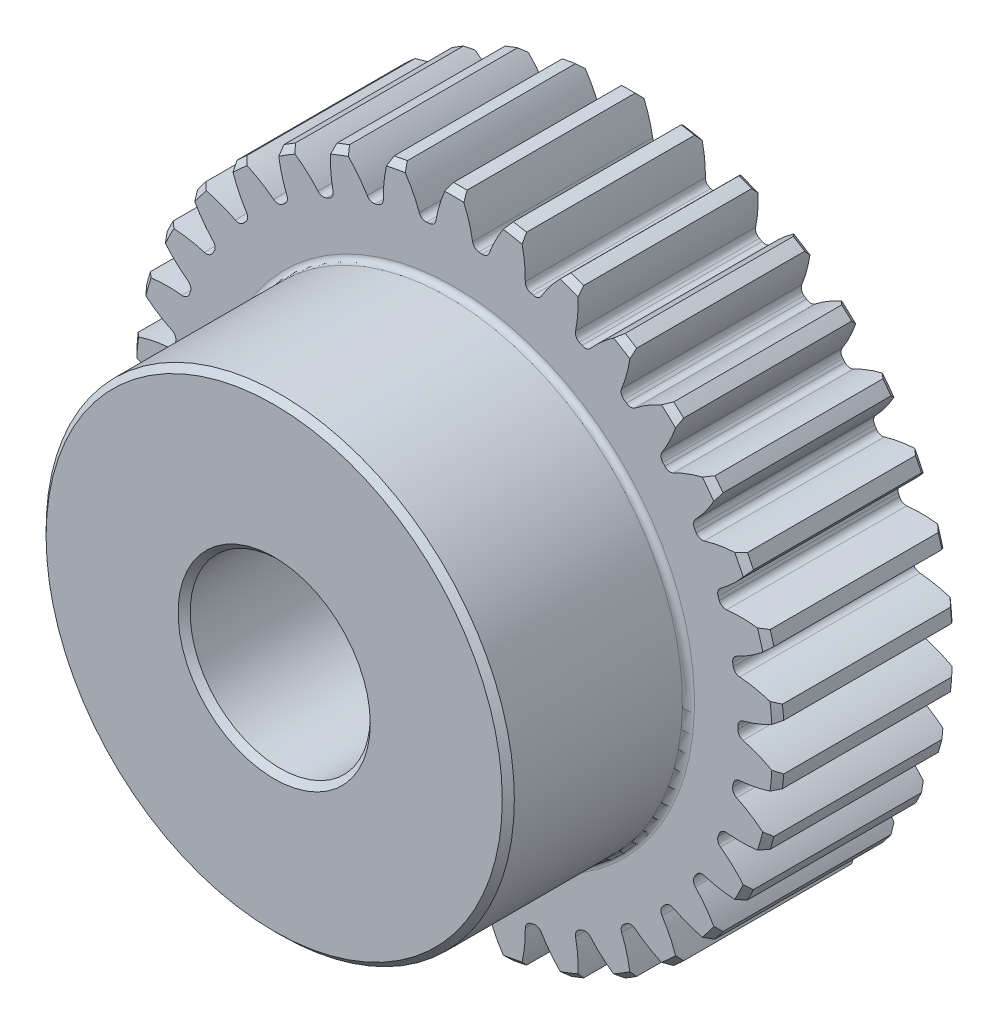
SolidWorks part; units mm, degrees
ref_plane "Front Plane" through (0, 0, 0) normal (0, 0, 1) x (1, 0, 0)
ref_plane "Top Plane" through (0, 0, 0) normal (0, 1, 0) x (1, 0, 0)
ref_plane "Right Plane" through (0, 0, 0) normal (1, 0, 0) x (0, 0, -1)
sketch "Sketch1" plane through (0, 0, 0) normal (0, 0, 1) x (1, 0, 0)
  line L0 (0, 0) -> (0, 17) construction
  line L1 (-5.4637, 18.9886) -> (5.4637, 15.0114) construction
  circle A0 centre (0, 0) radius 15.75 construction
  circle A1 centre (0, 0) radius 18 construction
  circle A2 centre (0, 0) radius 17 construction
  circle A3 centre (0, 0) radius 15.9748 construction
  circle A4 centre (0, 0) radius 13 construction
  circle A5 centre (0, 0) radius 5 construction
  point P8 (0.5, 0)
  point P13 (17, 0)
  dimension "OD" = 36
  dimension "Root Diameter" = 31.5
  dimension "Gear Pitch Diameter" = 34
  dimension "Base Diameter" = 31.9495
  dimension "Hub Diameter" = 26
  dimension "For Shaft Diameter" = 10
  dimension "Pressure Angle" = 20
  dimension "Number of Teeth" = 34
  dimension "Module" = 1
sketch "Sketch2" plane through (0, 0, 0) normal (1, 0, 0) x (0, 0, -1)
  line L0 (-10, 0) -> (10, 0) construction
  line L1 (10, 18) -> (10, -18) construction
  line L2 (0, -13) -> (-10, -13) construction
  line L3 (-10, 18) -> (10, 18) construction
  line L8 (-10, -13) -> (-10, 13) construction
  point P4 (0, 18)
  point P5 (-5, 0)
  dimension "Overall Width" = 20
  dimension "Hub Width" = 10
  dimension "Approx Set Screw Positon" = 5
  dimension "Face Width" = 10
sketch "Sketch3" plane through (0, 0, 0) normal (0, 0, 1) x (1, 0, 0)
  circle A0 centre (0, 0) radius 18
  circle A1 centre (0, 0) radius 18 construction
extrude "Boss-Extrude1" add sketch "Sketch3" against normal up to vertex (10 mm away) and the other way up to vertex (10 mm away) up to point (0, 0, -10) other way up to point (0, 0, 10)
sketch "Sketch5" plane through (0, 0, 0) normal (1, 0, 0) x (0, 0, -1)
  line L1 (0, 13) -> (-10, 13)
  line L2 (0, 13) -> (0, 18)
  line L3 (0, 18) -> (-10, 18)
  line L4 (-10, 13) -> (-10, 18)
  line L5 (-10, 0) -> (10, 0)
  line L6 (-10, 0) -> (-10, 5)
  line L7 (-10, 5) -> (10, 5)
  line L8 (10, 0) -> (10, 5)
  point P5 (0, 13)
  point P12 (0, 5)
revolve "Cut-Revolve1" cut sketch "Sketch5" angle 360 about L0
fillet "Fillet2" radius 0.3355 1 edges at (0, -13, 0)
chamfer "Chamfer1" distance 0.3355 angle 45 5 edges at (0, -5, -10) (0, -18, 0) (18, 0, -10) (0, -5, 10) (0, -13, 10)
sketch "Sketch4" plane through (0, 0, 0) normal (0, 0, 1) x (1, 0, 0)
  line L0 (15.7451, 0.3927) -> (15.7451, -0.3927)
  arc A3 (17.9539, 1.288) -> (17.9539, -1.288) centre (0, 0) cw
  circle A4 centre (0, 0) radius 18 construction
  arc A5 (15.7451, 0.3927) -> (17.9539, 1.288) centre (14.1683, 7.4547) ccw
  circle A8 centre (0, 0) radius 15.75 construction
  arc A9 (15.7451, -0.3927) -> (17.9539, -1.288) centre (14.1683, -7.4547) cw
  spline S0 degree 4 poles (15.967, 0.4999) (15.9701, 0.5) (15.9791, 0.5005) (15.9959, 0.5018) (16.0234, 0.5046) (16.0583, 0.5091) (16.1034, 0.5159) (16.1565, 0.5252) (16.2147, 0.5368) (16.2779, 0.551) (16.3409, 0.5664) (16.4036, 0.583) (16.4659, 0.6006) (16.5413, 0.6233) (16.6315, 0.6523) (16.7366, 0.6889) (16.8555, 0.7334) (16.9763, 0.7822) (17.0947, 0.8329) (17.2139, 0.8872) (17.329, 0.942) (17.448, 1.0022) (17.5576, 1.0593) (17.6798, 1.1269) (17.7783, 1.1824) (17.9076, 1.2595) (17.9837, 1.3061) (18.0726, 1.362) (18.112, 1.3875) (18.1362, 1.4032) knots 0 0 0 0 0 0.005377 0.015084 0.028532 0.04661 0.064855 0.092111 0.119476 0.146842 0.174209 0.201575 0.228941 0.256307 0.307035 0.361767 0.4165 0.471232 0.525964 0.580697 0.635429 0.690161 0.744894 0.799626 0.854358 0.909091 0.954545 1 1 1 1 1 construction
  spline S1 degree 4 poles (15.967, 0.4999) (15.9701, 0.5) (15.9791, 0.5005) (15.9959, 0.5018) (16.0234, 0.5046) (16.0583, 0.5091) (16.1034, 0.5159) (16.1565, 0.5252) (16.2147, 0.5368) (16.2779, 0.551) (16.3409, 0.5664) (16.4036, 0.583) (16.4659, 0.6006) (16.5413, 0.6233) (16.6315, 0.6523) (16.7366, 0.6889) (16.8555, 0.7334) (16.9763, 0.7822) (17.0947, 0.8329) (17.2139, 0.8872) (17.329, 0.942) (17.448, 1.0022) (17.5576, 1.0593) (17.6798, 1.1269) (17.7783, 1.1824) (17.8795, 1.2428) (17.9287, 1.2726) (17.9539, 1.288) knots 0 0 0 0 0 0.005377 0.015084 0.028532 0.04661 0.064855 0.092111 0.119476 0.146842 0.174209 0.201575 0.228941 0.256307 0.307035 0.361767 0.4165 0.471232 0.525964 0.580697 0.635429 0.690161 0.744894 0.799626 0.854358 0.909091 0.909091 0.909091 0.909091 0.909091 construction
  spline S2 degree 4 poles (15.967, -0.4999) (15.9701, -0.5) (15.9791, -0.5005) (15.9959, -0.5018) (16.0234, -0.5046) (16.0583, -0.5091) (16.1034, -0.5159) (16.1565, -0.5252) (16.2147, -0.5368) (16.2779, -0.551) (16.3409, -0.5664) (16.4036, -0.583) (16.4659, -0.6006) (16.5413, -0.6233) (16.6315, -0.6523) (16.7366, -0.6889) (16.8555, -0.7334) (16.9763, -0.7822) (17.0947, -0.8329) (17.2139, -0.8872) (17.329, -0.942) (17.448, -1.0022) (17.5576, -1.0593) (17.6798, -1.1269) (17.7783, -1.1824) (17.9076, -1.2595) (17.9837, -1.3061) (18.0726, -1.362) (18.112, -1.3875) (18.1362, -1.4032) knots 0 0 0 0 0 0.005377 0.015084 0.028532 0.04661 0.064855 0.092111 0.119476 0.146842 0.174209 0.201575 0.228941 0.256307 0.307035 0.361767 0.4165 0.471232 0.525964 0.580697 0.635429 0.690161 0.744894 0.799626 0.854358 0.909091 0.954545 1 1 1 1 1 construction
  spline S3 degree 4 poles (15.967, -0.4999) (15.9701, -0.5) (15.9791, -0.5005) (15.9959, -0.5018) (16.0234, -0.5046) (16.0583, -0.5091) (16.1034, -0.5159) (16.1565, -0.5252) (16.2147, -0.5368) (16.2779, -0.551) (16.3409, -0.5664) (16.4036, -0.583) (16.4659, -0.6006) (16.5413, -0.6233) (16.6315, -0.6523) (16.7366, -0.6889) (16.8555, -0.7334) (16.9763, -0.7822) (17.0947, -0.8329) (17.2139, -0.8872) (17.329, -0.942) (17.448, -1.0022) (17.5576, -1.0593) (17.6798, -1.1269) (17.7783, -1.1824) (17.8795, -1.2428) (17.9287, -1.2726) (17.9539, -1.288) knots 0 0 0 0 0 0.005377 0.015084 0.028532 0.04661 0.064855 0.092111 0.119476 0.146842 0.174209 0.201575 0.228941 0.256307 0.307035 0.361767 0.4165 0.471232 0.525964 0.580697 0.635429 0.690161 0.744894 0.799626 0.854358 0.909091 0.909091 0.909091 0.909091 0.909091 construction
  dimension "D1" = 0.7854
extrude "Cut-Extrude1" cut sketch "Sketch4" against normal through all both and the other way through all
fillet "Fillet1" radius 0.3927 2 edges at (15.7451, 0.3927, -5) (15.7451, -0.3927, -5)
pattern_circular "CirPattern1" count 34 over 360 about axis through (0, 0, 0) along (0, 0, 1) of "Cut-Extrude1", "Fillet1"
equation "\"Number of Teeth\"= 34"
equation "\"Module\"= 1"
equation "\"Diametral Pitch\"= 1 / \"Module\""
equation "\"Dedendum\"= 1.25 / \"Diametral Pitch\""
equation "\"Pitch Diameter\"= \"Module\" * \"Number of Teeth\""
equation "\"Root Diameter\"= \"Pitch Diameter\" - ( 2 * \"Dedendum\" )"
equation "\"Root Diameter@Sketch1\"=\"Root Diameter\""
equation "\"OD@Sketch1\" = \"Outside Diameter\""
equation "\"D1@CirPattern1\"=\"Number of Teeth\""
equation "\"Pressure Angle\"=20"
equation "\"Base Diameter\"= \"Pitch Diameter\" * cos ( \"Pressure Angle\" )"
equation "\"Outside Diameter\"= ( \"Number of Teeth\" + 2 ) / \"Diametral Pitch\""
equation "\"Pitch Angle\"= 360deg / \"Number of Teeth\""
equation "\"Alpha\"= sqr ( \"Pitch Diameter\" ^ 2 - \"Base Diameter\" ^ 2 ) / \"Base Diameter\" * 180 / PI - \"Pressure Angle\""
equation "\"Beta\"= ( \"Pitch Angle\" / 4 - \"Alpha\" )"
equation "\"Phi\"= sqr ( ( \"Outside Diameter\" / 2 ) ^ 2 - ( \"Base Diameter\" / 2 ) ^ 2 ) / ( \"Base Diameter\" / 2 )"
equation "\"Addendum\"= 1 / \"Diametral Pitch\""
equation "\"WorkingDepth\"= 2 / \"Diametral Pitch\""
equation "\"WholeDepth\"= 2.25 / \"Diametral Pitch\""
equation "\"Clearance\"= 0.25 / \"Diametral Pitch\""
equation "\"ToothThickness\"= ( pi * 2 ) / \"Diametral Pitch\""
equation "\"CircularPitch\"= pi / \"Diametral Pitch\""
equation "\"Number of Teeth@Sketch1\"=\"Number of Teeth\""
equation "\"Module@Sketch1\"=\"Module\""
equation "\"Pressure Angle@Sketch1\"=\"Pressure Angle\""
equation "\"Gear Pitch Diameter@Sketch1\"=\"Pitch Diameter\""
equation "\"Base Diameter@Sketch1\"=\"Base Diameter\""
equation "\"Fillet\"= \"Clearance\" * cos ( \"Pressure Angle\" ) * tan ( ( 90 + \"Pressure Angle\" ) / 2 )"
equation "\"D1@Fillet2\"=\"Fillet\""
equation "\"Approx Set Screw Positon@Sketch2\" = \"Hub Width@Sketch2\" / 2"
equation "\"D2\"= \"Fillet\" * 2"
equation "\"D1@Chamfer1\"=\"Fillet\""
equation "\"D1@Sketch4\"=\"CircularPitch\"*0.25"
equation "\"D1@Fillet1\"=\"CircularPitch\"*0.125"
